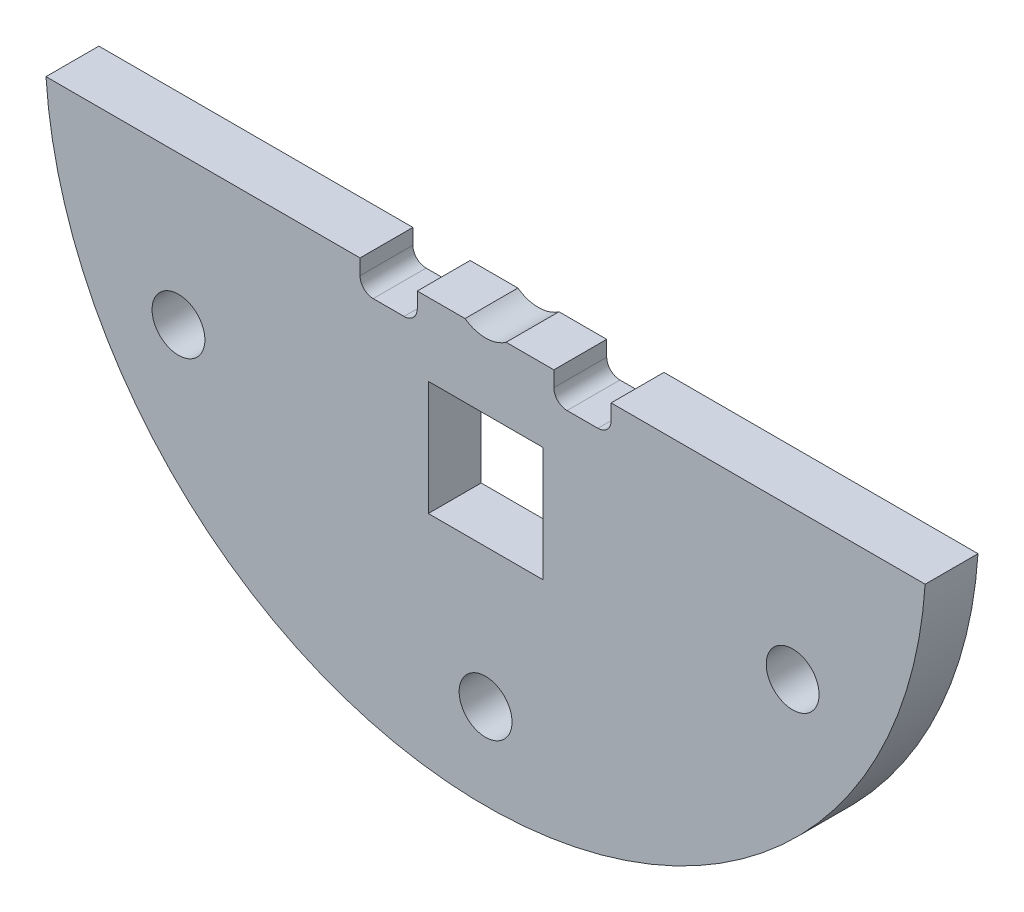
SolidWorks part; units mm, degrees
ref_plane "Alzado" through (0, 0, 0) normal (0, 0, 1) x (1, 0, 0)
ref_plane "Planta" through (0, 0, 0) normal (0, 1, 0) x (1, 0, 0)
ref_plane "Vista lateral" through (0, 0, 0) normal (1, 0, 0) x (0, 0, -1)
sketch "Model" plane through (0, 0, 0) normal (0, 0, 1) x (1, 0, 0)
  line L0 (191.3969, 188.9643) -> (194.1059, 188.9643)
  line L1 (186.3559, 188.9643) -> (189.065, 188.9643)
  line L2 (193.4809, 184.8393) -> (186.9809, 184.8393)
  line L3 (186.9809, 184.8393) -> (186.9809, 178.3393)
  line L4 (186.9809, 178.3393) -> (193.4809, 178.3393)
  line L5 (193.4809, 178.3393) -> (193.4809, 184.8393)
  line L6 (185.6059, 187.3393) -> (183.8559, 187.3393)
  line L7 (186.3559, 188.9643) -> (186.3559, 188.0893)
  line L8 (197.3559, 188.0893) -> (197.3559, 188.9643)
  line L9 (194.8559, 187.3393) -> (196.6059, 187.3393)
  line L10 (194.1059, 188.9643) -> (194.1059, 188.0893)
  line L11 (165.2838, 188.9643) -> (183.1059, 188.9643)
  line L12 (197.3559, 188.9643) -> (215.1781, 188.9643)
  line L13 (183.1059, 188.0893) -> (183.1059, 188.9643)
  arc A0 (165.2838, 188.9643) -> (193.4809, 165.8014) centre (190.2309, 190.5893) ccw
  arc A1 (193.4809, 165.8014) -> (215.1781, 188.9643) centre (190.2309, 190.5893) ccw
  arc A2 (189.065, 188.9643) -> (191.3969, 188.9643) centre (190.2309, 190.5893) ccw
  circle A4 centre (172.8025, 180.527) radius 1.5
  circle A5 centre (190.2309, 170.4647) radius 1.5
  circle A6 centre (207.6594, 180.527) radius 1.5
  arc A7 (183.1059, 188.0893) -> (183.8559, 187.3393) centre (183.8559, 188.0893) ccw
  arc A8 (185.6059, 187.3393) -> (186.3559, 188.0893) centre (185.6059, 188.0893) ccw
  arc A9 (196.6059, 187.3393) -> (197.3559, 188.0893) centre (196.6059, 188.0893) ccw
  arc A10 (194.1059, 188.0893) -> (194.8559, 187.3393) centre (194.8559, 188.0893) ccw
extrude "Saliente-Extruir1" add sketch "Model" along normal blind 3
